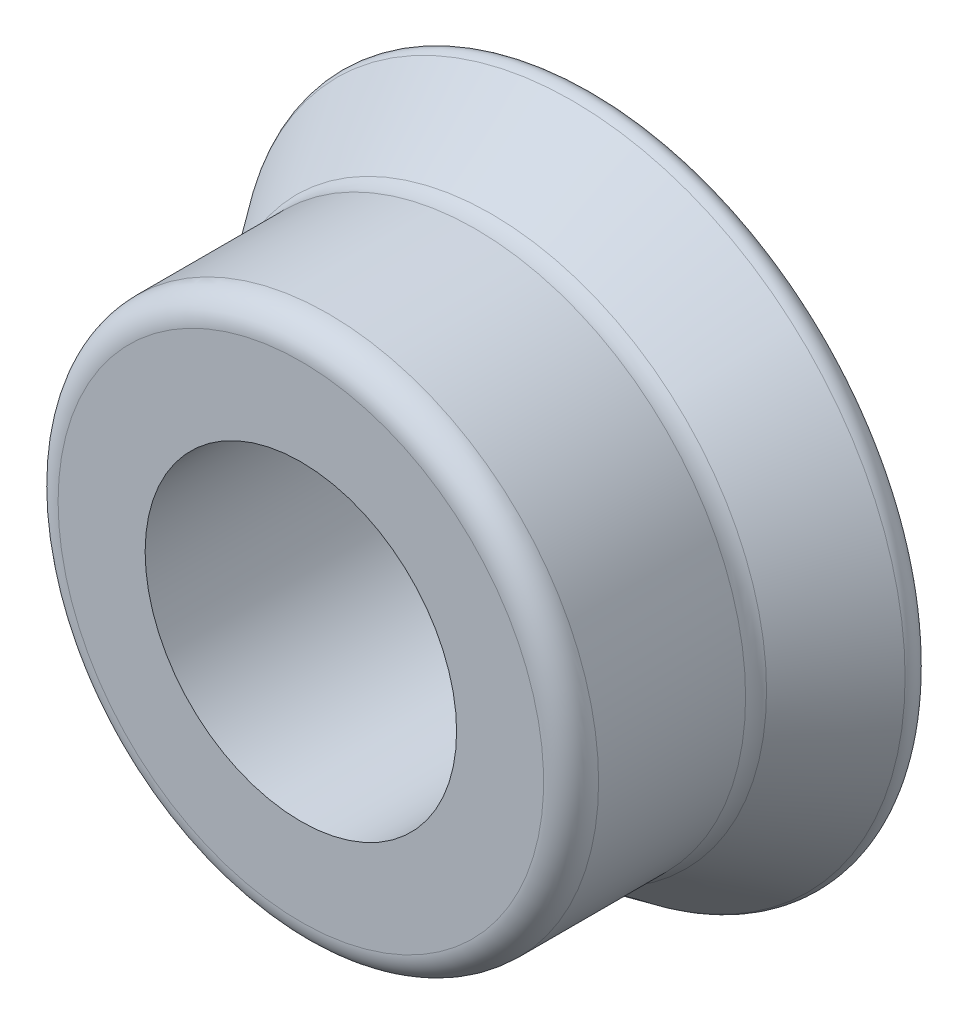
SolidWorks part; units mm, degrees
material "球墨铸铁 QT400-18"
ref_plane "前视基准面" through (0, 0, 0) normal (0, 0, 1) x (1, 0, 0)
ref_plane "上视基准面" through (0, 0, 0) normal (0, 1, 0) x (1, 0, 0)
ref_plane "右视基准面" through (0, 0, 0) normal (1, 0, 0) x (0, 0, -1)
sketch "草图1" plane through (0, 0, 0) normal (1, 0, 0) x (0, 0, -1)
  line L0 (0, 0) -> (-6.4502, 0) construction
  line L1 (0, 0) -> (0, -3.5099)
  line L2 (-0.2367, -3.6323) -> (-1.1221, -3.0052)
  line L3 (-1.2955, -2.95) -> (-3.4, -2.95)
  line L4 (-3.7, -2.65) -> (-3.7, 0)
  line L5 (0, 0) -> (-3.7, 0)
  arc A0 (0, -3.5099) -> (-0.2367, -3.6323) centre (-0.15, -3.5099) cw
  arc A1 (-3.4, -2.95) -> (-3.7, -2.65) centre (-3.4, -2.65) cw
  arc A2 (-1.1221, -3.0052) -> (-1.2955, -2.95) centre (-1.2955, -3.25) ccw
  point P1 (-1.5334, -2.95)
  point P10 (0, -3.8)
  point P13 (-3.7, -2.95)
  point P16 (-1.2, -2.95)
  dimension "D5" = 0.15
  dimension "D6" = 0.3
  dimension "D7" = 0.3
  dimension "D1" = 3.7
  dimension "D2" = 7.6
  dimension "D3" = 5.9
  dimension "D4" = 2.5
revolve "旋转1" add sketch "草图1" angle 360 about L0
hole_wizard "M3 六角头螺栓的柱形沉头孔1" positions "3D草图4" profile "草图7" counterbore size "M3" standard "GB"
sketch3d "3D草图4"
  line L0 (0, 0, 5.0699) -> (0, 0, 0.0603) construction
  point P0 (0, 0, 3.7)
sketch "草图7" plane through (0, 0, 3.7) normal (1, 0, 0) x (0, -1, 0)
  line L0 (0, 0) -> (0, 4.7205)
  line L1 (0, 4.7205) -> (1.7, 3.699)
  line L2 (1.7, 3.699) -> (1.7, 0.5)
  line L3 (1.7, 0.5) -> (4.5, 0.5)
  line L4 (4.5, 0.5) -> (4.5, 0)
  line L5 (4.5, 0) -> (0, 0)
  line L10 (0, 4.7205) -> (-1.7, 3.699) construction
  line L11 (0, -6.35) -> (0, 107.95) construction
  dimension "孔直径" = 3.4
  dimension "孔深度" = 3.699
  dimension "柱形沉头孔直径" = 9
  dimension "柱形沉头孔深度" = 0.5
  dimension "导头角度" = 118
fillet "圆角2" radius 0.3 1 edges at (-2.95, 0, 3.2)
